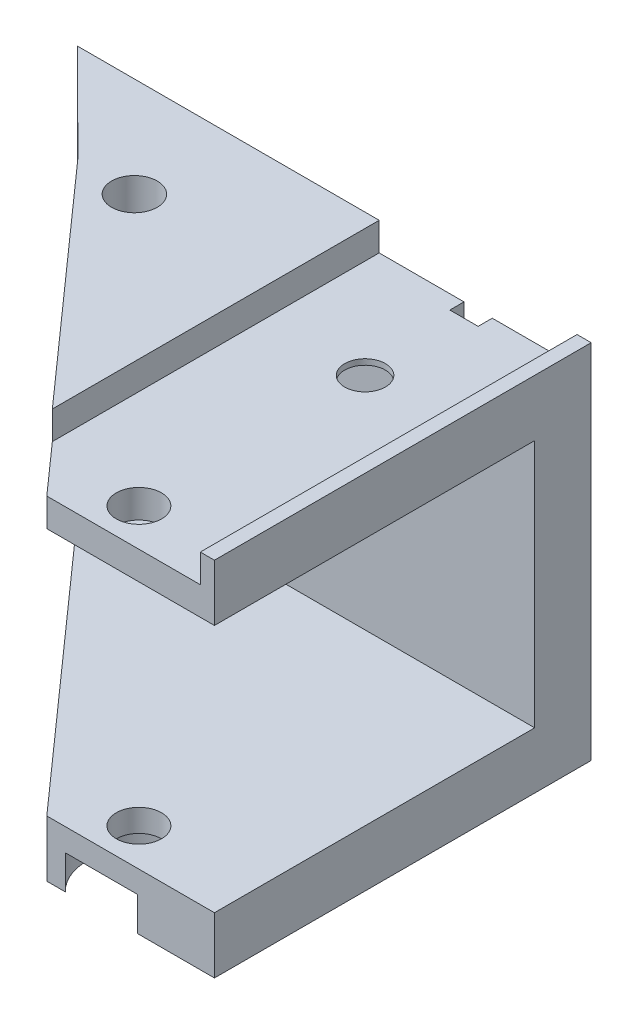
SolidWorks part; units mm, degrees
ref_plane "Front Plane" through (0, 0, 0) normal (0, 0, 1) x (1, 0, 0)
ref_plane "Top Plane" through (0, 0, 0) normal (0, 1, 0) x (1, 0, 0)
ref_plane "Right Plane" through (0, 0, 0) normal (1, 0, 0) x (0, 0, -1)
sketch "Sketch2" plane through (0, 0, 0) normal (0, 1, 0) x (1, 0, 0)
  line L0 (0, 0) -> (50.8, 0)
  line L1 (50.8, 0) -> (50.8, -57.15)
  line L2 (50.8, -57.15) -> (0, 0)
  circle A0 centre (38.1, -6.35) radius 2.286
  circle A1 centre (38.1, -31.75) radius 2.54
  circle A2 centre (10.6999, -4.8572) radius 2.54
  dimension "D1" = 0
  dimension "D5" = 12.7
  dimension "D6" = 25.4
  dimension "D2" = 25.4
  dimension "D3" = 50.8
  dimension "D4" = 57.15
extrude "Boss-Extrude1" add sketch "Sketch2" along normal blind 6.35
sketch "Sketch3" plane through (0, 0, 0) normal (0, 0, -1) x (-1, 0, 0)
  line L1 (-50.8, 0) -> (0, 0)
  line L2 (-50.8, 0) -> (-50.8, -27.94)
  line L3 (-50.8, -27.94) -> (0, -27.94)
  line L4 (0, 0) -> (0, -27.94)
  dimension "D1" = 27.94
extrude "Boss-Extrude2" add sketch "Sketch3" along normal blind 6.35
sketch "Sketch5" plane through (0, 6.35, 0) normal (0, 1, 0) x (1, 0, 0)
  line L1 (0, 0) -> (50.8, 0)
  line L2 (0, 0) -> (0, 6.35)
  line L3 (0, 6.35) -> (50.8, 6.35)
  line L4 (50.8, 0) -> (50.8, 6.35)
extrude "Boss-Extrude3" add sketch "Sketch5" against normal blind 6.35
sketch "Sketch6" plane through (0, 0, 0) normal (0, -1, 0) x (1, 0, 0)
  circle A0 centre (38.1, 6.35) radius 6.35
extrude "Cut-Extrude1" cut sketch "Sketch6" against normal blind 2.54 and the other way blind 38.1
sketch "Sketch7" plane through (0, -27.94, 0) normal (0, -1, 0) x (1, 0, 0)
  line L0 (50.8, 0) -> (0, 0) construction
  line L1 (0, -6.35) -> (50.8, -6.35)
  line L2 (0, -6.35) -> (0, 0)
  line L3 (0, 0) -> (50.8, 0)
  line L4 (50.8, -6.35) -> (50.8, 0)
  line L5 (38.1, 0) -> (50.8, 0) construction
  line L6 (0, 0) -> (50.8, 57.15)
  line L7 (50.8, 57.15) -> (50.8, 0)
  line L8 (0, 0) -> (50.8, 0)
  circle A0 centre (38.1, 31.75) radius 2.54
extrude "Boss-Extrude4" add sketch "Sketch7" along normal blind 6.35
sketch "Sketch8" plane through (0, 6.35, 0) normal (0, 1, 0) x (1, 0, 0)
  line L0 (26.9875, 6.35) -> (49.2125, 6.35)
  line L1 (50.8, 6.35) -> (0, 6.35) construction
  line L2 (38.1, -6.35) -> (38.1, 6.35) construction
  line L3 (38.1, 6.35) -> (38.1, -38.669) construction
  line L4 (26.9875, 6.35) -> (26.9875, -30.3609)
  line L5 (0, 0) -> (50.8, -57.15) construction
  line L6 (49.2125, 6.35) -> (49.2125, -55.3641)
  line L7 (49.2125, -55.3641) -> (26.9875, -30.3609)
  point P8 (38.1, 6.35)
  dimension "D1" = 22.225
  dimension "D2" = 0
extrude "Cut-Extrude2" cut sketch "Sketch8" against normal blind 3.175
sketch "Sketch9" plane through (0, 6.35, 0) normal (0, 1, 0) x (1, 0, 0)
  circle A0 centre (10.6999, -4.8572) radius 2.5643
extrude "Cut-Extrude3" cut sketch "Sketch9" against normal blind 127
sketch "Sketch11" plane through (0, 0, -6.35) normal (0, 0, -1) x (-1, 0, 0)
  line L6 (-49.2125, 3.175) -> (-26.9875, 3.175) construction
  line L7 (-39.6875, 3.175) -> (-36.5125, 3.175)
  line L8 (-39.6875, 3.175) -> (-39.6875, -34.29)
  line L9 (-39.6875, -34.29) -> (-36.5125, -34.29)
  line L10 (-36.5125, 3.175) -> (-36.5125, -34.29)
  line L11 (0, -34.29) -> (-50.8, -34.29) construction
  dimension "D1" = 9.525
  dimension "D2" = 9.525
extrude "Cut-Extrude4" cut sketch "Sketch11" against normal blind 1.5875
sketch "Sketch16" plane through (0, -34.29, 0) normal (0, -1, 0) x (1, 0, 0)
  circle A0 centre (38.1, 31.75) radius 5.842
extrude "Cut-Extrude7" cut sketch "Sketch16" against normal blind 3.81
sketch "Sketch17" plane through (0, 6.35, 0) normal (0, 1, 0) x (1, 0, 0)
  line L0 (50.8, -57.15) -> (50.8, 6.35) construction
  line L1 (50.8, -35.9671) -> (31.6086, -35.9671)
  line L2 (50.8, -35.9671) -> (50.8, -57.15)
  line L3 (50.8, -57.15) -> (31.6086, -57.15)
  line L4 (31.6086, -35.9671) -> (31.6086, -57.15)
  line L5 (3.9924, -4.4914) -> (14.8338, 6.35)
  line L6 (0, 0) -> (26.9875, -30.3609) construction
  line L7 (26.9875, 6.35) -> (0, 6.35) construction
  line L8 (14.8338, 6.35) -> (0, 6.35)
  line L9 (0, 6.35) -> (0, 0) construction
  line L10 (0, 6.35) -> (0, 0)
  line L11 (0, 0) -> (3.9924, -4.4914)
extrude "Cut-Extrude8" cut sketch "Sketch17" against normal through all
sketch "Sketch18" plane through (0, 6.35, 0) normal (0, 1, 0) x (1, 0, 0)
  line L0 (14.8338, 6.35) -> (-6.9155, 6.35)
  line L1 (-6.9155, 6.35) -> (3.9924, -4.4914)
  line L6 (26.9875, 6.35) -> (14.8338, 6.35)
  line L7 (14.8338, 6.35) -> (3.9924, -4.4914)
  line L8 (3.9924, -4.4914) -> (26.9875, -30.3609)
  line L9 (26.9875, -30.3609) -> (26.9875, 6.35)
  line L11 (14.8338, 6.35) -> (3.9924, -4.4914)
  dimension "D1" = 0
extrude "Boss-Extrude5" add sketch "Sketch18" against normal up to surface (40.64 mm away) up to face at (34.6361, -34.29, 9.3978)
sketch "Sketch19" plane through (0, 6.35, 0) normal (0, 1, 0) x (1, 0, 0)
  circle A0 centre (10.6999, -4.8572) radius 2.5643
